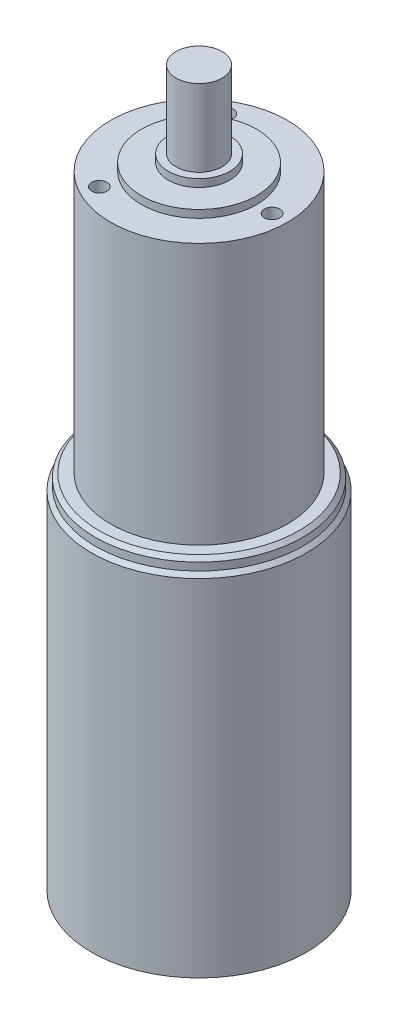
SolidWorks part; units mm, degrees
ref_plane "Face" through (0, 0, 0) normal (0, 0, 1) x (1, 0, 0)
ref_plane "Dessus" through (0, 0, 0) normal (0, 1, 0) x (1, 0, 0)
ref_plane "Droite" through (0, 0, 0) normal (1, 0, 0) x (0, 0, -1)
sketch "Esquisse1" plane through (0, 0, 0) normal (0, 0, 1) x (1, 0, 0)
  line L0 (0, 0) -> (0, 93) construction
  line L1 (0, 0) -> (14, 0)
  line L2 (14, 17) -> (14, 0)
  line L4 (14, 17) -> (14, 45)
  line L5 (14, 45) -> (13.5, 45.5)
  line L6 (13.5, 45.5) -> (13.5, 46.5)
  line L7 (13.5, 46.5) -> (13, 47)
  line L8 (13, 47) -> (11.5, 47)
  line L9 (11.5, 47) -> (11.5, 81)
  line L10 (11.5, 81) -> (7.5, 81)
  line L11 (7.5, 81) -> (7.5, 82)
  line L12 (7.5, 82) -> (4, 82)
  line L13 (4, 82) -> (4, 83)
  line L14 (4, 83) -> (3, 83)
  line L15 (3, 83) -> (3, 93)
  line L16 (3, 93) -> (0, 93)
  line L17 (0, 0) -> (0, 93)
  point P5 (0, 0)
  dimension "D1" = 6
  dimension "D2" = 10
  dimension "D3" = 17
  dimension "D4" = 28
  dimension "D5" = 23
  dimension "D6" = 27
  dimension "D7" = 15
  dimension "D8" = 8
  dimension "D10" = 28
  dimension "D11" = 47
  dimension "D12" = 0.5
  dimension "D13" = 0.5
  dimension "D14" = 34
  dimension "D15" = 1
  dimension "D16" = 1
revolve "Révolution1" add sketch "Esquisse1" angle 360 about L0
sketch "Esquisse3" plane through (0, 81, 0) normal (0, 1, 0) x (1, 0, 0)
  line L0 (0, 0) -> (9.5, 0) construction
  line L1 (0, 0) -> (-4.75, 8.2272) construction
  line L2 (0, 0) -> (-4.75, -8.2272) construction
  circle A1 centre (0, 0) radius 9.5 construction
  circle A2 centre (9.5, 0) radius 1
  circle A3 centre (-4.75, -8.2272) radius 1
  circle A4 centre (-4.75, 8.2272) radius 1
  dimension "D1" = 19
  dimension "D2" = 2
  dimension "D3" = 120
  dimension "D4" = 120
extrude "Enlèv. mat.-Extru.1" cut sketch "Esquisse3" against normal blind 5
